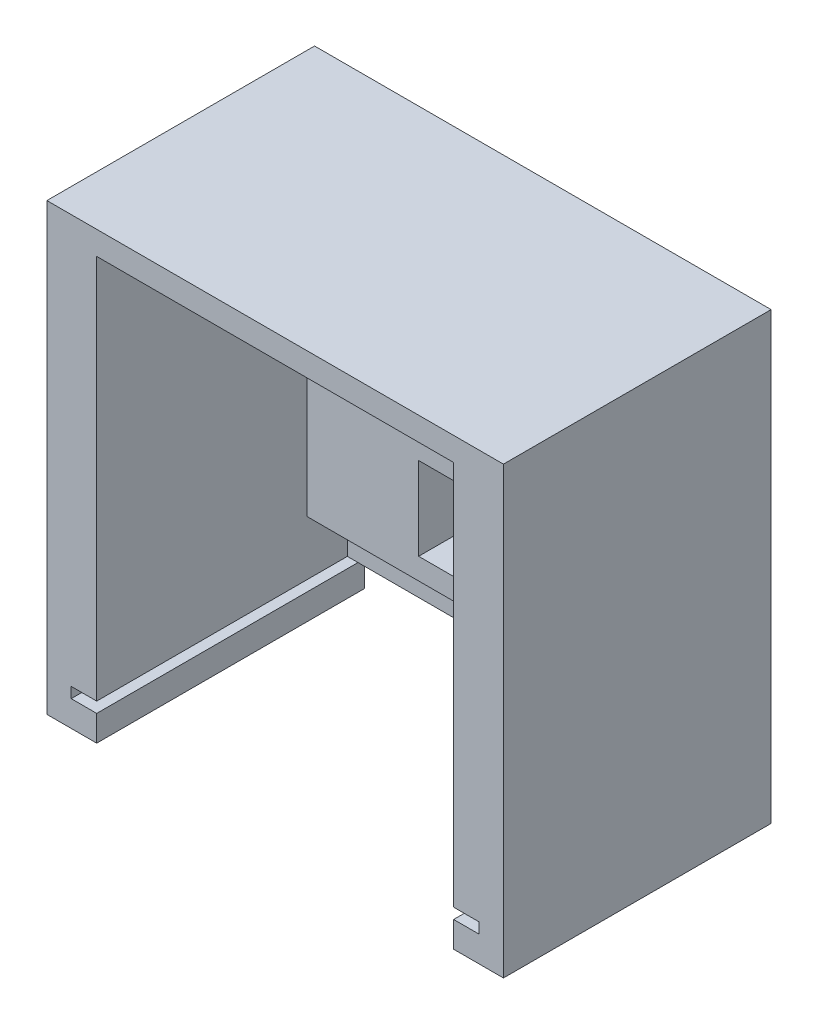
SolidWorks part; units mm, degrees
ref_plane "Front Plane" through (0, 0, 0) normal (0, 0, 1) x (1, 0, 0)
ref_plane "Top Plane" through (0, 0, 0) normal (0, 1, 0) x (1, 0, 0)
ref_plane "Right Plane" through (0, 0, 0) normal (1, 0, 0) x (0, 0, -1)
sketch "Sketch1" plane through (0, 0, 0) normal (0, 0, 1) x (1, 0, 0)
  line L0 (0, 0) -> (0, 166.26)
  line L1 (0, 166.26) -> (-170.56, 166.26)
  line L2 (-170.56, 166.26) -> (-170.56, 0)
  line L3 (-170.56, 0) -> (-151.95, 0)
  line L4 (0, 0) -> (-18.61, 0)
  line L5 (-151.95, 0) -> (-151.95, 9.64)
  line L6 (-18.61, 0) -> (-18.61, 9.64)
  line L7 (-151.95, 9.64) -> (-161.48, 9.64)
  line L8 (-18.61, 9.64) -> (-9.08, 9.64)
  line L9 (-161.48, 9.64) -> (-161.48, 13.61)
  line L10 (-9.08, 9.64) -> (-9.08, 13.61)
  line L11 (-161.48, 13.61) -> (-151.95, 13.61)
  line L12 (-151.95, 13.61) -> (-151.95, 157.49)
  line L13 (-9.08, 13.61) -> (-18.61, 13.61)
  line L14 (-18.61, 13.61) -> (-18.61, 157.49)
  line L15 (-18.61, 157.49) -> (-151.95, 157.49)
  dimension "D1" = 166.26
  dimension "D2" = 170.56
  dimension "D3" = 18.61
  dimension "D4" = 9.64
  dimension "D5" = 9.53
  dimension "D6" = 3.97
  dimension "D7" = 8.77
extrude "Boss-Extrude1" add sketch "Sketch1" along normal blind 100
sketch "Sketch2" plane through (0, 0, 0) normal (0, 0, -1) x (-1, 0, 0)
  line L1 (18.61, 157.49) -> (151.95, 157.49)
  line L2 (18.61, 157.49) -> (18.61, 13.61)
  line L3 (18.61, 13.61) -> (151.95, 13.61)
  line L4 (151.95, 157.49) -> (151.95, 13.61)
extrude "Boss-Extrude2" add sketch "Sketch2" against normal blind 6.35
sketch "Sketch3" plane through (0, 0, 6.35) normal (0, 0, 1) x (1, 0, 0)
  line L0 (-151.95, 13.61) -> (-151.95, 157.49) construction
  line L1 (-151.95, 33.97) -> (-64.61, 33.97)
  line L2 (-151.95, 33.97) -> (-151.95, 90.94)
  line L3 (-151.95, 90.94) -> (-64.61, 90.94)
  line L4 (-64.61, 33.97) -> (-64.61, 90.94)
  line L5 (-151.95, 157.49) -> (-18.61, 157.49) construction
  dimension "D1" = 87.34
  dimension "D2" = 56.97
  dimension "D3" = 66.55
extrude "Boss-Extrude3" add sketch "Sketch3" along normal blind 15
sketch "Sketch4" plane through (0, 0, 6.35) normal (0, 0, 1) x (1, 0, 0)
  line L0 (-151.95, 90.94) -> (-151.95, 157.49) construction
  line L1 (-64.61, 90.94) -> (-151.95, 90.94) construction
  line L2 (-18.61, 13.61) -> (-151.95, 13.61) construction
  line L3 (-18.61, 157.49) -> (-18.61, 13.61) construction
  circle A0 centre (-56.5025, 39.0354) radius 4.5
  circle A1 centre (-144.2275, 97.9829) radius 4.5
  dimension "D1" = 9
  dimension "D2" = 7.7225
  dimension "D3" = 7.0429
  dimension "D4" = 25.4254
  dimension "D5" = 37.8925
extrude "Cut-Extrude1" cut sketch "Sketch4" against normal through all
sketch "Sketch5" plane through (0, 0, 21.35) normal (0, 0, 1) x (1, 0, 0)
  line L0 (-64.61, 90.94) -> (-151.95, 90.94) construction
  line L1 (-110.33, 72.95) -> (-70.33, 72.95)
  line L2 (-110.33, 72.95) -> (-110.33, 41.95)
  line L3 (-110.33, 41.95) -> (-70.33, 41.95)
  line L4 (-70.33, 72.95) -> (-70.33, 41.95)
  line L5 (-64.61, 33.97) -> (-64.61, 90.94) construction
  dimension "D1" = 31
  dimension "D2" = 17.99
  dimension "D3" = 40
  dimension "D4" = 5.72
extrude "Cut-Extrude2" cut sketch "Sketch5" against normal through all contours L2 L3 L4 L1
sketch "Sketch6" plane through (0, 0, 6.35) normal (0, 0, 1) x (1, 0, 0)
  line L1 (-151.95, 157.49) -> (-18.61, 157.49) construction
  line L2 (-77.52, 157.49) -> (-77.52, 135.02)
  line L3 (-77.52, 135.02) -> (-72.88, 135.02)
  line L4 (-72.88, 135.02) -> (-72.88, 107.08)
  line L5 (-72.88, 107.08) -> (-98.28, 107.08)
  line L6 (-98.28, 107.08) -> (-98.28, 135.02)
  line L7 (-98.28, 135.02) -> (-93.64, 135.02)
  line L8 (-93.64, 135.02) -> (-93.64, 157.49)
  line L9 (-93.64, 157.49) -> (-77.52, 157.49)
  line L10 (-18.61, 157.49) -> (-18.61, 13.61) construction
  dimension "D1" = 22.47
  dimension "D2" = 27.94
  dimension "D3" = 16.12
  dimension "D4" = 25.4
  dimension "D5" = 54.27
extrude "Cut-Extrude3" cut sketch "Sketch6" against normal blind 2.545 contours L8 L9 L2 L3 L4 L5 L6 L7
sketch "Sketch7" plane through (0, 0, 3.805) normal (0, 0, 1) x (1, 0, 0)
  line L0 (-72.88, 107.08) -> (-98.28, 107.08) construction
  line L1 (-89.93, 126.67) -> (-81.22, 126.67)
  line L2 (-89.93, 126.67) -> (-89.93, 117.96)
  line L3 (-89.93, 117.96) -> (-81.22, 117.96)
  line L4 (-81.22, 126.67) -> (-81.22, 117.96)
  line L5 (-72.88, 135.02) -> (-72.88, 107.08) construction
  dimension "D1" = 8.71
  dimension "D2" = 10.88
  dimension "D3" = 8.34
extrude "Cut-Extrude4" cut sketch "Sketch7" against normal through all
